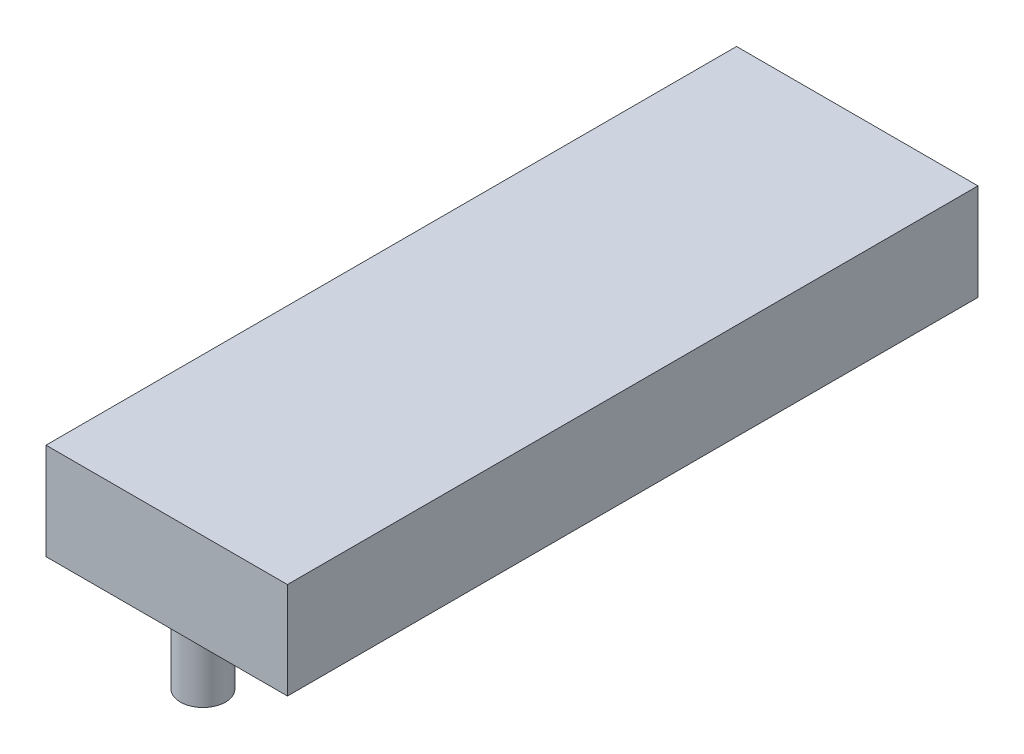
SolidWorks part; units mm, degrees
ref_plane "Front Plane" through (0, 0, 0) normal (0, 0, 1) x (1, 0, 0)
ref_plane "Top Plane" through (0, 0, 0) normal (0, 1, 0) x (1, 0, 0)
ref_plane "Right Plane" through (0, 0, 0) normal (1, 0, 0) x (0, 0, -1)
sketch "Sketch1" plane through (0, 0, 0) normal (0, 1, 0) x (1, 0, 0)
  line L1 (-5, -14.3) -> (5, -14.3)
  line L2 (-5, -14.3) -> (-5, 14.3)
  line L3 (-5, 14.3) -> (5, 14.3)
  line L4 (5, -14.3) -> (5, 14.3)
  line L5 (-5, -14.3) -> (5, 14.3) construction
  line L6 (-5, 14.3) -> (5, -14.3) construction
  point P0 (0, 0)
  dimension "D1" = 10
  dimension "D2" = 28.6
extrude "Boss-Extrude1" add sketch "Sketch1" along normal blind 4
sketch "Sketch2" plane through (0, 0, 0) normal (0, -1, 0) x (1, 0, 0)
  line L0 (0, -2.2) -> (0, 2.2) construction
  line L1 (-5, 14.3) -> (5, 14.3) construction
  line L2 (2.2, 0) -> (-2.2, 0) construction
  circle A0 centre (0, 12.8) radius 0.935
  circle A1 centre (0, -12.8) radius 0.935
  dimension "D2" = 1.87
  dimension "D1" = 1.5
extrude "Boss-Extrude2" add sketch "Sketch2" along normal blind 3
